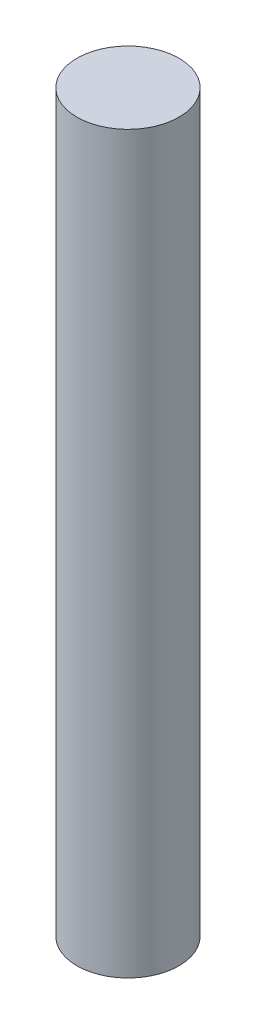
SolidWorks part; units mm, degrees
ref_plane "Front Plane" through (0, 0, 0) normal (0, 0, 1) x (1, 0, 0)
ref_plane "Top Plane" through (0, 0, 0) normal (0, 1, 0) x (1, 0, 0)
ref_plane "Right Plane" through (0, 0, 0) normal (1, 0, 0) x (0, 0, -1)
sketch "Sketch1" plane through (0, 0, 0) normal (0, 1, 0) x (1, 0, 0)
  circle A1 centre (0, 0) radius 3.9688
  point P5 (-1.5721, 4.8306)
  point P6 (0, 0)
  point P7 (0, 0)
  point P8 (0, 0)
  dimension "D1" = 7.9375
extrude "Boss-Extrude1" add sketch "Sketch1" along normal blind 57.15
